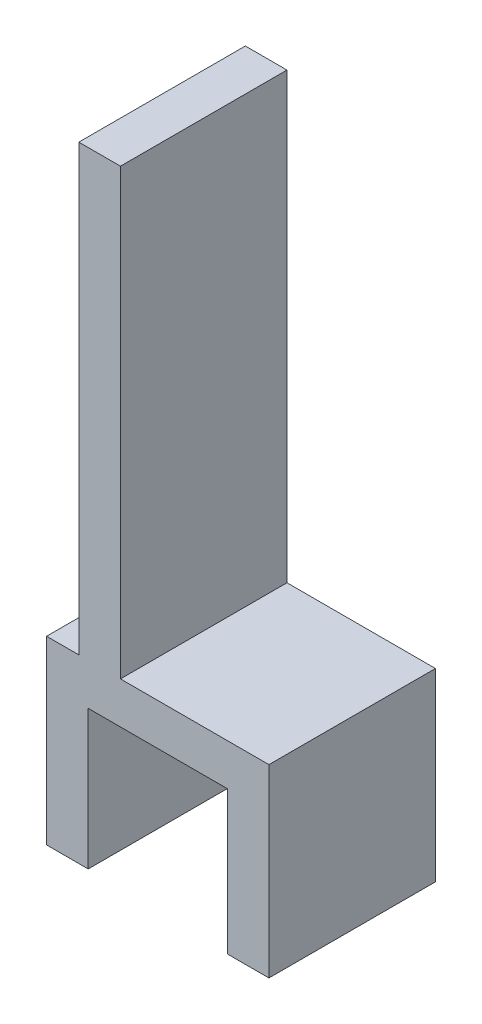
SolidWorks part; units mm, degrees
ref_plane "Front Plane" through (0, 0, 0) normal (0, 0, 1) x (1, 0, 0)
ref_plane "Top Plane" through (0, 0, 0) normal (0, 1, 0) x (1, 0, 0)
ref_plane "Right Plane" through (0, 0, 0) normal (1, 0, 0) x (0, 0, -1)
sketch "Sketch1" plane through (0, 0, 0) normal (0, 0, 1) x (1, 0, 0)
  line L0 (0, 30.7563) -> (0, -18.2981) construction
  line L1 (-24.2352, 0) -> (31.9243, 0) construction
  line L2 (0, -13.025) -> (0, 0)
  line L3 (0, 0) -> (2.325, 0)
  line L4 (2.325, 0) -> (2.325, 32)
  line L5 (2.325, 32) -> (5.325, 32)
  line L6 (5.325, 32) -> (5.325, 0)
  line L7 (5.325, 0) -> (16.025, 0)
  line L8 (16.025, 0) -> (16.025, -13.317)
  line L9 (16.025, -13.317) -> (13.025, -13.317)
  line L10 (13.025, -13.317) -> (13.025, -3)
  line L11 (13.025, -3) -> (3, -3)
  line L12 (3, -3) -> (3, -13.025)
  line L13 (3, -13.025) -> (0, -13.025)
  dimension "D1" = 10.025
  dimension "D2" = 10.025
  dimension "D3" = 3
  dimension "D4" = 3
  dimension "D5" = 3
  dimension "D6" = 3
  dimension "D7" = 32
  dimension "D8" = 2.325
extrude "Boss-Extrude1" add sketch "Sketch1" along normal blind 12
sketch "Sketch2" plane through (0, 0, 0) normal (1, 0, 0) x (0, 0, -1)
  line L0 (-6, 36.7298) -> (-6, -19.3123) construction
  line L1 (-12, -13.317) -> (0, -13.317) construction
  circle A0 centre (-6, -6.817) radius 1.75
  dimension "D2" = 3.5
  dimension "D3" = 6.5
  dimension "D1" = 6
